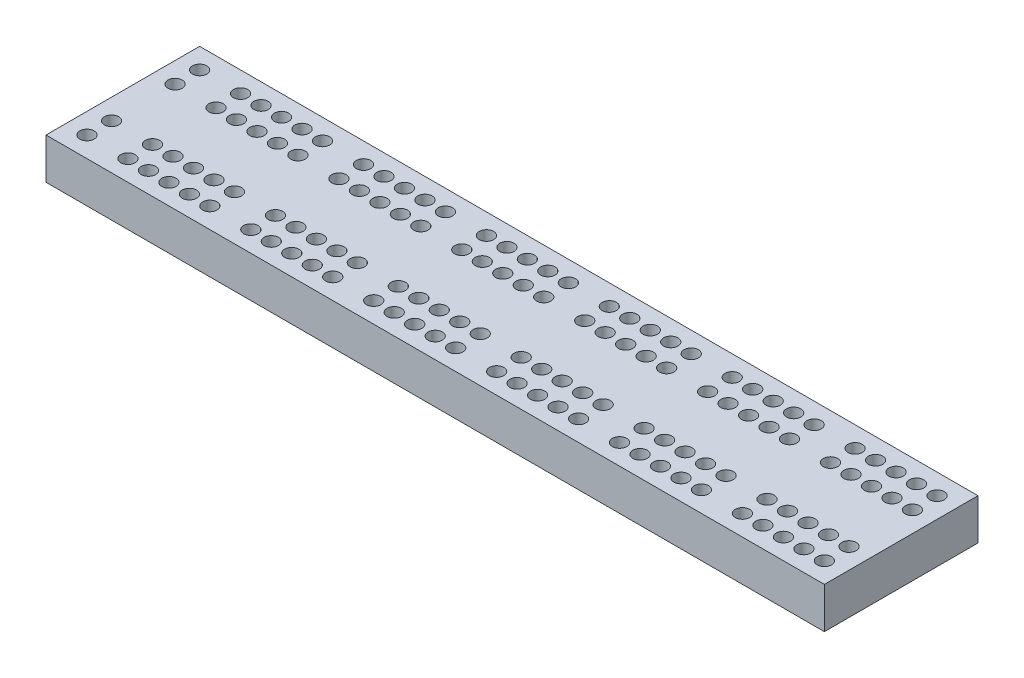
SolidWorks part; units mm, degrees
ref_plane "前基準面" through (0, 0, 0) normal (0, 0, 1) x (1, 0, 0)
ref_plane "上基準面" through (0, 0, 0) normal (0, 1, 0) x (1, 0, 0)
ref_plane "右基準面" through (0, 0, 0) normal (1, 0, 0) x (0, 0, -1)
sketch "草圖1" plane through (0, 0, 0) normal (0, 0, 1) x (1, 0, 0)
  line L1 (0, 10) -> (380, 10)
  line L2 (0, 10) -> (0, -10)
  line L3 (0, -10) -> (380, -10)
  line L4 (380, 10) -> (380, -10)
  dimension "D1" = 380
  dimension "D2" = 20
extrude "填料-伸長1" add sketch "草圖1" along normal mid plane 75
hole_wizard "Ø7.0 (7) 直徑孔1" positions "草圖2" profile "草圖3" hole size "Ø7.0" standard "ISO"
sketch "草圖2" plane through (0, 10, 0) normal (0, 1, 0) x (1, 0, 0)
  line L0 (0, -37.5) -> (0, 37.5) construction
  line L1 (380, 37.5) -> (0, 37.5) construction
  point P0 (10, 27.5)
  dimension "D1" = 10
  dimension "D2" = 10
sketch "草圖3" plane through (10, 10, -27.5) normal (1, 0, 0) x (0, 0, 1)
  line L0 (0, 0) -> (0, 14.103)
  line L1 (0, 14.103) -> (3.5, 12)
  line L2 (3.5, 12) -> (3.5, 0)
  line L5 (3.5, 0) -> (0, 0)
  line L10 (0, 14.103) -> (-3.5, 12) construction
  line L11 (0, -6.35) -> (0, 107.95) construction
  dimension "鑽孔直徑" = 7
  dimension "鑽孔深度" = 12
  dimension "導頭角度" = 118
pattern_linear "直線複製排列1" count 37 spacing 10 along (1, 0, 0) count 2 spacing 12 along (0, 0, 1) skipping (1, 0), (1, 1), (7, 0), (7, 1), (13, 0), (13, 1), (19, 0), (19, 1), (25, 0), (25, 1), (31, 0), (31, 1) of "Ø7.0 (7) 直徑孔1"
mirror "鏡射1" about plane through (0, 0, 0) normal (0, 0, 1) of "直線複製排列1", "Ø7.0 (7) 直徑孔1"
